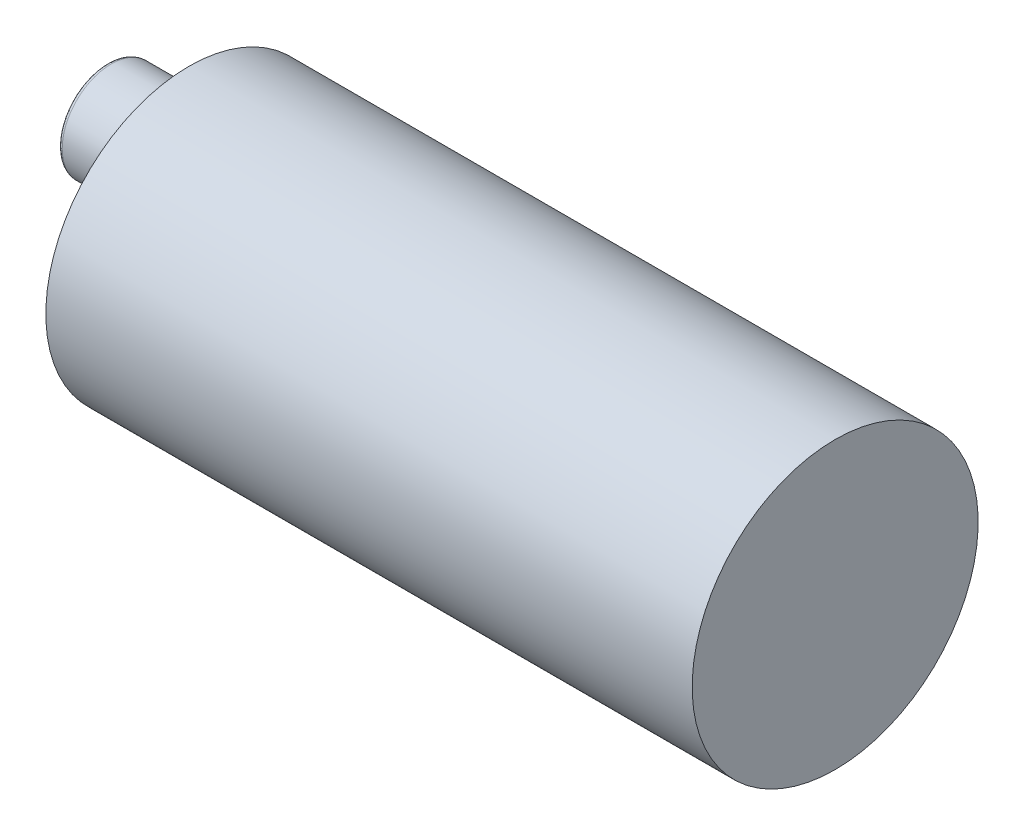
SolidWorks part; units mm, degrees
ref_plane "Ön Düzlem" through (0, 0, 0) normal (0, 0, 1) x (1, 0, 0)
ref_plane "Üst Düzlem" through (0, 0, 0) normal (0, 1, 0) x (1, 0, 0)
ref_plane "Sağ Düzlem" through (0, 0, 0) normal (1, 0, 0) x (0, 0, -1)
sketch "Sketch1" plane through (0, 0, 0) normal (0, 0, 1) x (1, 0, 0)
  line L1 (-52.9414, 7.1828) -> (26.1586, 7.1828)
  line L2 (-52.9414, 7.1828) -> (-52.9414, -10.3172)
  line L3 (-52.9414, -10.3172) -> (26.1586, -10.3172)
  line L4 (26.1586, 7.1828) -> (26.1586, -10.3172)
  dimension "D1" = 17.5
  dimension "D2" = 79.1
revolve "Revolve1" add sketch "Sketch1" angle 360 about L1
sketch "Sketch2" plane through (-52.9414, 0, 0) normal (-1, 0, 0) x (0, 0, 1)
  line L0 (0, 7.1828) -> (0, 14.1828)
  circle A0 centre (0, 14.1828) radius 6
  dimension "D2" = 12
  dimension "D1" = 7
extrude "Boss-Extrude1" add sketch "Sketch2" along normal blind 10
fillet "Fillet2" radius 0.5 1 edges at (-62.9414, 14.1828, 6)
sketch "Sketch3" plane through (-62.9414, 0, 0) normal (-1, 0, 0) x (0, 0, 1)
  circle A0 centre (0, 14.1828) radius 3
  dimension "D1" = 6
extrude "Cut-Extrude3" cut sketch "Sketch3" against normal blind 3
